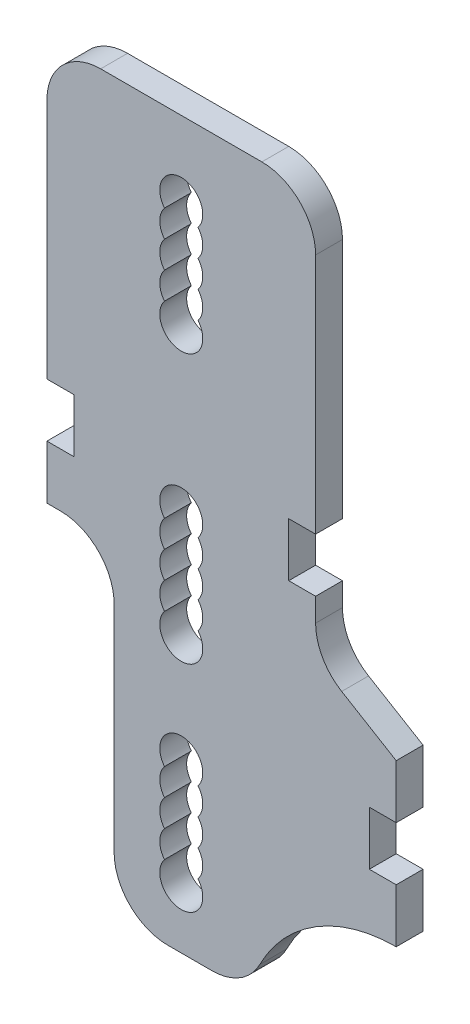
SolidWorks part; units mm, degrees
ref_plane "Front Plane" through (0, 0, 0) normal (1, 0, 0) x (0, 1, 0)
ref_plane "Top Plane" through (0, 0, 0) normal (0, 0, 1) x (0, 1, 0)
ref_plane "Right Plane" through (0, 0, 0) normal (0, 1, 0) x (-1, 0, 0)
sketch "Sketch1" plane through (0, 0, 0) normal (0, 0, 1) x (0, 1, 0)
  line L4 (0, 0) -> (0, 25) construction
  line L5 (0, 25) -> (10, 25)
  line L6 (10, 25) -> (10, 20)
  line L7 (10, 20) -> (20, 20)
  line L8 (20, 20) -> (20, 25)
  line L9 (20, 25) -> (75, 25)
  line L10 (75, 25) -> (75, -25)
  line L12 (20, -25) -> (20, -20)
  line L13 (20, -20) -> (10, -20)
  line L14 (10, -20) -> (10, -25)
  line L15 (10, -25) -> (0, -25)
  line L16 (0, -25) -> (0, 0) construction
  line L17 (15, 20) -> (15, -20) construction
  line L18 (15, 0) -> (46, 0) construction
  line L19 (20, -25) -> (75, -25)
  line L20 (46, 0) -> (-4, 0) construction
  line L21 (-4, 0) -> (-44, 0) construction
  line L22 (0, 25) -> (0, 12.5)
  line L23 (0, 12.5) -> (-60, 12.5)
  line L24 (-24, 0) -> (-24, -40) construction
  line L25 (-60, 12.5) -> (-60, -12.5)
  line L29 (-24, -40) -> (-24, -37.5) construction
  line L30 (-39, -40) -> (-29, -40)
  line L31 (-24, -40) -> (-19, -40) construction
  line L32 (-29, -40) -> (-29, -35)
  line L33 (-29, -35) -> (-19, -35)
  line L34 (-19, -40) -> (-19, -35)
  line L35 (-29, -40) -> (-19, -35) construction
  line L36 (-29, -35) -> (-19, -40) construction
  line L37 (-9, -40) -> (0, -25)
  line L38 (-39, -40) -> (-60, -12.5) construction
  line L39 (-29, -40) -> (-24, -40) construction
  line L40 (-19, -40) -> (-9, -40)
  line L41 (-29, -40) -> (-24, -40) construction
  line L42 (-24, -40) -> (-19, -40) construction
  line L43 (-49.5, -26.25) -> (-44.8503, -22.6993) construction
  line L44 (-39, -40) -> (-39, -27.5353) construction
  circle A3 centre (46, 0) radius 4
  circle A4 centre (-44, 0) radius 4
  circle A5 centre (-4, 0) radius 4
  arc A6 (-60, -12.5) -> (-39, -40) centre (-67.506, -40) cw
  circle A7 centre (-9, 0) radius 4
  circle A8 centre (-49, 0) radius 4
  circle A9 centre (41, 0) radius 4
  circle A10 centre (-4, 0) radius 4
  circle A11 centre (-44, 0) radius 4
  circle A12 centre (46, 0) radius 4
  circle A13 centre (1, 0) radius 4
  circle A14 centre (-39, 0) radius 4
  circle A15 centre (51, 0) radius 4
  circle A16 centre (6, 0) radius 4
  circle A17 centre (-34, 0) radius 4
  circle A18 centre (56, 0) radius 4
  circle A19 centre (1, 0) radius 4
  circle A20 centre (-39, 0) radius 4
  circle A21 centre (51, 0) radius 4
  circle A22 centre (6, 0) radius 4
  circle A23 centre (-34, 0) radius 4
  circle A24 centre (56, 0) radius 4
  circle A25 centre (11, 0) radius 4
  circle A26 centre (-29, 0) radius 4
  circle A27 centre (61, 0) radius 4
  point P38 (-24, -40)
  dimension "D3" = 10
  dimension "D4" = 10
  dimension "D8" = 8
  dimension "D10" = 40
  dimension "D16" = 30
  dimension "D1" = 25
  dimension "D2" = 25
  dimension "D5" = 5
  dimension "D6" = 60
  dimension "D7" = 46
  dimension "D9" = 31
  dimension "D11" = 50
  dimension "D12" = 40
  dimension "D13" = 25
  dimension "D14" = 60
extrude "Boss-Extrude1" add sketch "Sketch1" along normal mid plane 5 contours L25 A6 L30 L32 L33 L34 L40 L37 L15 L14 L13 L12 L19 L10 L9 L8 L7 L6 L5 L22 L23 A27 A18 A15 A3 A9 A26 A17 A14 A4 A8 A25 A16 A13 A5 A7
fillet "Fillet1" radius 10 6 edges at (-12.5, 0, 0) (25, 0, 0) (12.5, -60, 0) (-12.5, -60, 0) (-25, 75, 0) (25, 75, 0)
